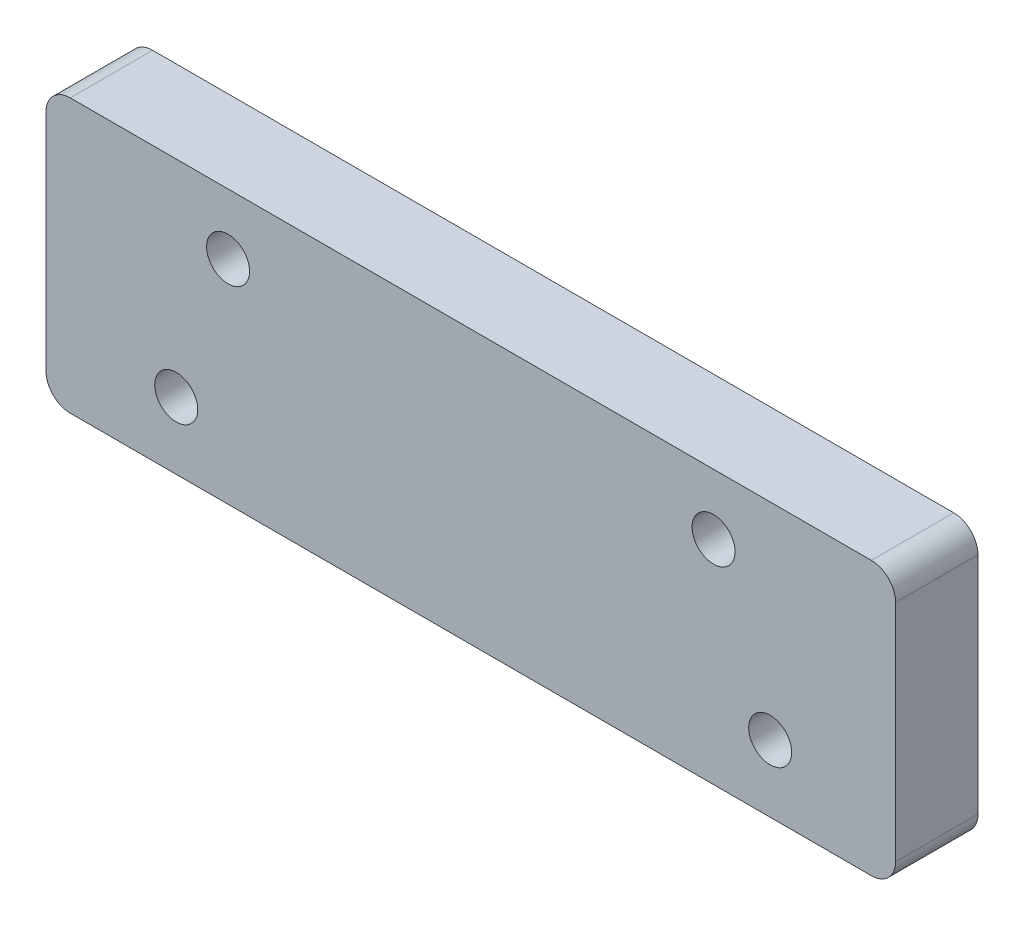
SolidWorks part; units mm, degrees
material "Custom Plastic"
ref_plane "X-Y Datum" through (0, 0, 0) normal (0, 0, 1) x (1, 0, 0)
ref_plane "X-Z Datum" through (0, 0, 0) normal (0, 1, 0) x (1, 0, 0)
ref_plane "Y-Z Datum" through (0, 0, 0) normal (1, 0, 0) x (0, 0, -1)
sketch "Sketch1" plane through (0, 0, 0) normal (0, 0, 1) x (1, 0, 0)
  line L0 (61.9, 0) -> (61.9, 14.5333) construction
  line L1 (106.35, 15.875) -> (17.45, 15.875)
  line L2 (106.35, 15.875) -> (106.35, 0)
  line L3 (106.35, 0) -> (17.45, 0)
  line L4 (17.45, 15.875) -> (17.45, 0)
  line L5 (106.35, 15.875) -> (17.45, 0) construction
  line L6 (106.35, 0) -> (17.45, 15.875) construction
  line L7 (87.225, 0) -> (36.575, 0) construction
  point P0 (61.9, 7.9375)
  point P9 (31.075, 7)
  point P13 (93.225, 7)
  dimension "D1" = 88.9
  dimension "D2" = 15.875
extrude "Boss-Extrude1" add sketch "Sketch1" against normal blind 7.62
hole_wizard "CBORE for M4 SHCS1" positions "Sketch2" profile "Sketch3" counterbore size "M4" standard "ANSI Metric" end condition through all
sketch "Sketch2" plane through (0, 0, -7.62) normal (0, 0, -1) x (-1, 0, 0)
  point P0 (-93.225, 7)
  point P3 (-31.075, 7)
sketch "Sketch3" plane through (93.225, 7, -7.62) normal (1, 0, 0) x (0, 1, 0)
  line L0 (0, 0) -> (0, 7.62)
  line L1 (0, 7.62) -> (2.25, 7.62)
  line L3 (2.25, 7.62) -> (2.25, 4)
  line L4 (2.25, 4) -> (4, 4)
  line L5 (4, 4) -> (4, 0)
  line L7 (4, 0) -> (0, 0)
  line L11 (0, -6.35) -> (0, 107.95) construction
  dimension "Thru Hole Dia." = 4.5
  dimension "Thru Hole Depth" = 7.62
  dimension "C'Bore Dia." = 8
  dimension "C'Bore Depth" = 4
sketch "Sketch4" plane through (0, 0, -7.62) normal (0, 0, -1) x (-1, 0, 0)
  line L4 (-17.45, 0) -> (-17.45, 15.875)
  line L5 (-17.45, 15.875) -> (-106.35, 15.875)
  line L6 (-106.35, 15.875) -> (-106.35, 0)
  line L7 (-106.35, 0) -> (-17.45, 0)
  line L8 (-17.45, 0) -> (-17.45, 15.875)
  line L9 (-17.45, 15.875) -> (-106.35, 15.875)
  line L10 (-106.35, 15.875) -> (-106.35, 0)
  line L11 (-106.35, 0) -> (-17.45, 0)
  circle A0 centre (-31.075, 7) radius 4 construction
  circle A1 centre (-93.225, 7) radius 4 construction
  circle A2 centre (-31.075, 7) radius 4
  circle A3 centre (-93.225, 7) radius 4
  dimension "D1" = 0
extrude "Boss-Extrude2" add sketch "Sketch4" along normal blind 1 contours L8 L9 L10 L11
sketch "Sketch5" plane through (0, 0, 0) normal (0, 0, 1) x (1, 0, 0)
  line L0 (106.35, 0) -> (106.35, 15.875) construction
  line L1 (17.45, 15.875) -> (106.35, 15.875)
  line L2 (17.45, 15.875) -> (17.45, 28.575)
  line L3 (17.45, 28.575) -> (106.35, 28.575)
  line L4 (106.35, 15.875) -> (106.35, 28.575)
  line L5 (17.45, 22.225) -> (106.35, 22.225) construction
  line L6 (61.9, 15.875) -> (61.9, 28.575) construction
  circle A0 centre (36.5, 22.225) radius 2
  circle A1 centre (87.3, 22.225) radius 2
  point P15 (0, 0)
  line M10 (106.35, 15.875) -> (17.45, 15.875)
  dimension "D2" = 4
  dimension "D1" = 12.7
  dimension "D3" = 25.4
extrude "Boss-Extrude3" add sketch "Sketch5" against normal blind 8.62 contours L4 L3 L2 A0 A1 M10 | A0 | A1
hole_wizard "M4 Clearance Hole1" positions "Sketch8" profile "Sketch9" hole size "M4" standard "ANSI Metric" end condition through all
sketch "Sketch8" plane through (0, 0, 0) normal (0, 0, 1) x (1, 0, 0)
  point P0 (36.5, 22.225)
  point P3 (87.3, 22.225)
sketch "Sketch9" plane through (36.5, 22.225, 0) normal (1, 0, 0) x (0, -1, 0)
  line L0 (0, 0) -> (0, 8.62)
  line L1 (0, 8.62) -> (2.25, 8.62)
  line L2 (2.25, 8.62) -> (2.25, 0)
  line L5 (2.25, 0) -> (0, 0)
  line L11 (0, -6.35) -> (0, 107.95) construction
  dimension "Thru Hole Dia." = 4.5
  dimension "Thru Hole Depth" = 8.62
fillet "Fillet1" radius 2.54 4 edges at (106.35, 28.575, -4.31) (106.35, 0, -4.31) (17.45, 0, -4.31) (17.45, 28.575, -4.31)
